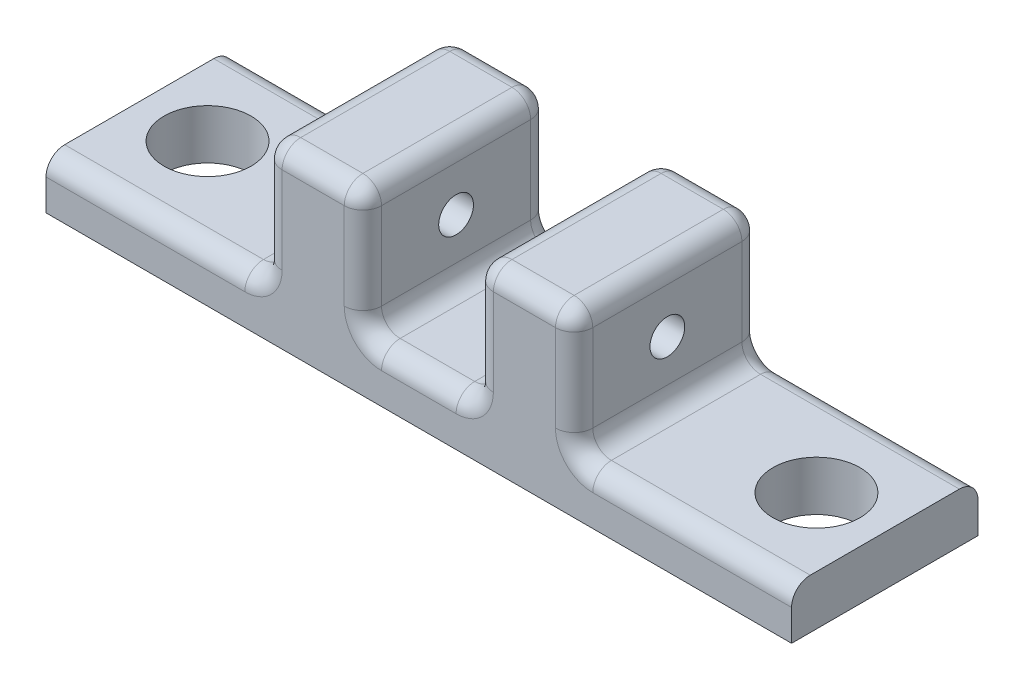
SolidWorks part; units mm, degrees
ref_plane "Front" through (0, 0, 0) normal (0, 0, 1) x (1, 0, 0)
ref_plane "Top" through (0, 0, 0) normal (0, 1, 0) x (1, 0, 0)
ref_plane "Right" through (0, 0, 0) normal (1, 0, 0) x (0, 0, -1)
sketch "Sketch3" plane through (0, 0, 0) normal (0, 1, 0) x (1, 0, 0)
  line L1 (-30, 7.5) -> (30, 7.5)
  line L2 (-30, 7.5) -> (-30, -7.5)
  line L3 (-30, -7.5) -> (30, -7.5)
  line L4 (30, 7.5) -> (30, -7.5)
  line L5 (-30, 7.5) -> (30, -7.5) construction
  line L6 (-30, -7.5) -> (30, 7.5) construction
  circle A0 centre (-24.5, 0) radius 3.5
  circle A1 centre (24.5, 0) radius 3.5
  point P0 (0, 0)
  point P11 (-30, 0)
  dimension "D2" = 7
  dimension "D3" = 7
  dimension "D1" = 60
  dimension "D4" = 5.5
  dimension "D5" = 5.5
  dimension "D6" = 15
extrude "Boss-Extrude1" add sketch "Sketch3" along normal blind 4
sketch "Sketch6" plane through (0, 4, 0) normal (0, 1, 0) x (1, 0, 0)
  line L0 (30, 7.5) -> (-30, 7.5) construction
  line L1 (-12.5, -7.5) -> (-4.5, -7.5)
  line L2 (-12.5, -7.5) -> (-12.5, 7.5)
  line L3 (-12.5, 7.5) -> (-4.5, 7.5)
  line L4 (-4.5, -7.5) -> (-4.5, 7.5)
  line L5 (-30, -7.5) -> (30, -7.5) construction
  point P8 (-12.5, 0)
  dimension "D1" = 8
  dimension "D2" = 12.5
extrude "Boss-Extrude2" add sketch "Sketch6" along normal blind 10
mirror "Mirror1" about plane through (0, 0, 0) normal (1, 0, 0) of "Boss-Extrude2"
fillet "Fillet2" radius 1.5 26 edges at (4.5, 4, 0) (-4.5, 4, 0) (-4.5, 9, -7.5) (4.5, 9, 7.5) (4.5, 9, -7.5) (21.25, 4, -7.5) (21.25, 4, 7.5) (0, 4, -7.5) (0, 4, 7.5) (4.5, 14, 0) (12.5, 14, 0) (12.5, 4, 0) (12.5, 9, -7.5) (12.5, 9, 7.5) (8.5, 14, -7.5) (8.5, 14, 7.5) (-4.5, 9, 7.5) (-4.5, 14, 0) (-12.5, 4, 0) (-21.25, 4, -7.5) (-12.5, 9, -7.5) (-12.5, 14, 0) (-12.5, 9, 7.5) (-21.25, 4, 7.5) (-8.5, 14, -7.5) (-8.5, 14, 7.5)
sketch "Sketch7" plane through (-12.5, 0, 0) normal (-1, 0, 0) x (0, 0, 1)
  circle A0 centre (0, 8.8706) radius 1.4
  dimension "D1" = 2.8
extrude "Cut-Extrude1" cut sketch "Sketch7" against normal through all both and the other way through all
